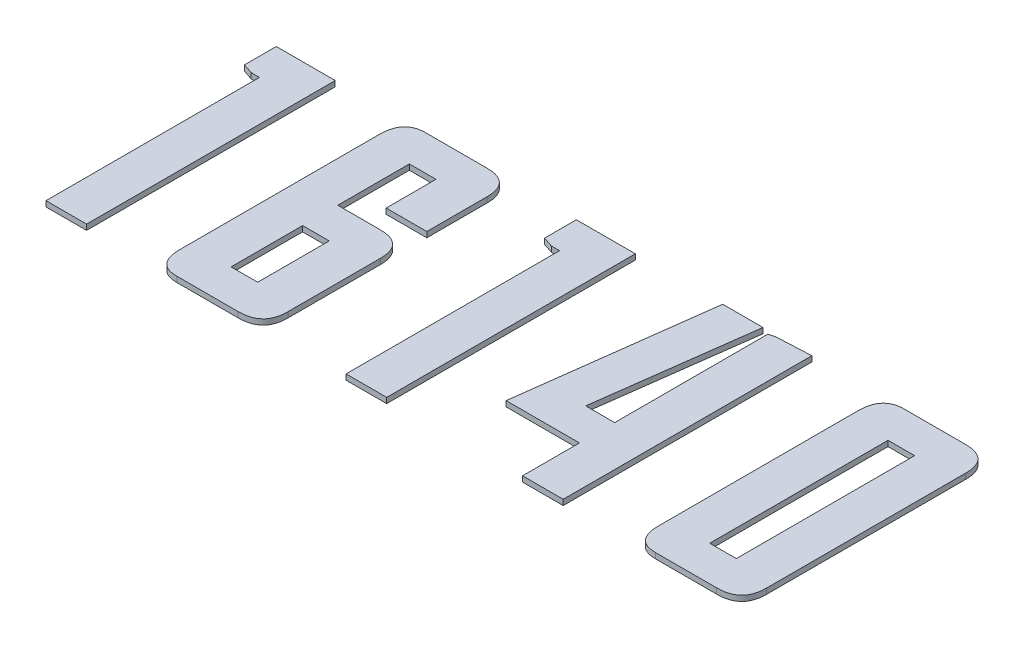
SolidWorks part; units mm, degrees
ref_plane "Front" through (0, 0, 0) normal (0, 0, 1) x (1, 0, 0)
ref_plane "Top" through (0, 0, 0) normal (0, 1, 0) x (1, 0, 0)
ref_plane "Right" through (0, 0, 0) normal (1, 0, 0) x (0, 0, -1)
sketch "Sketch1" plane through (0, 0, 0) normal (0, 1, 0) x (1, 0, 0)
  text T0 "<b>16140</b>" font "ViolentaSolidW01-Regular" height in points 150
extrude "Boss-Extrude1" add sketch "Sketch1" along normal blind 1.2
